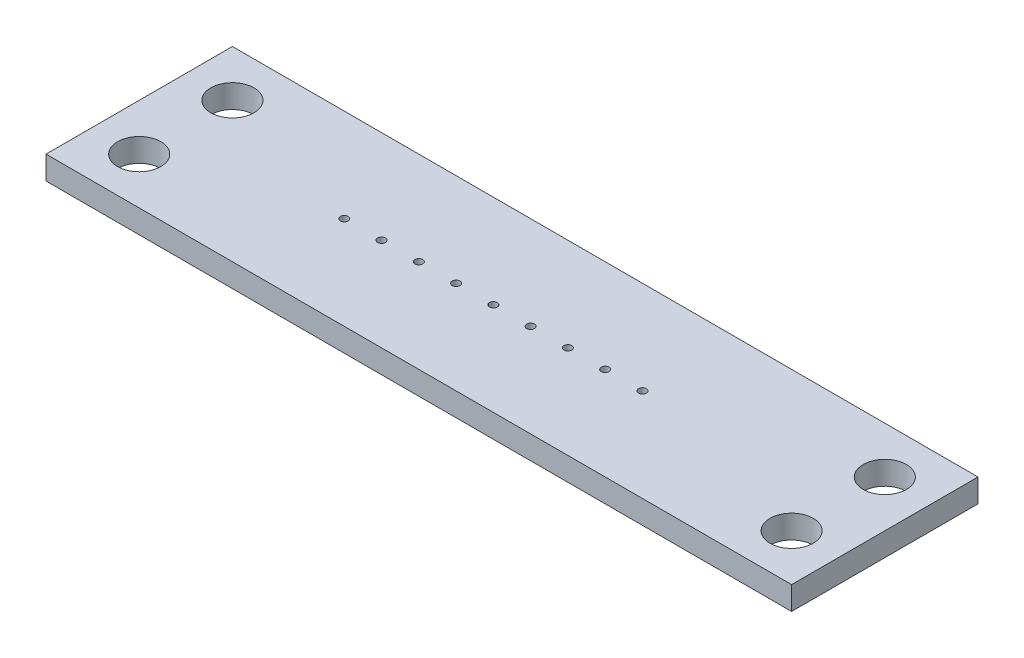
SolidWorks part; units mm, degrees
ref_plane "Front" through (0, 0, 0) normal (0, 0, 1) x (1, 0, 0)
ref_plane "Top" through (0, 0, 0) normal (0, 1, 0) x (1, 0, 0)
ref_plane "Right" through (0, 0, 0) normal (1, 0, 0) x (0, 0, -1)
sketch "Sketch1" plane through (0, 0, 0) normal (0, 1, 0) x (1, 0, 0)
  line L1 (0, 0) -> (50.8, 0)
  line L2 (0, 0) -> (0, 12.7)
  line L3 (0, 12.7) -> (50.8, 12.7)
  line L4 (50.8, 0) -> (50.8, 12.7)
  dimension "D1" = 12.7
  dimension "D2" = 50.8
extrude "Boss-Extrude1" add sketch "Sketch1" along normal blind 1.5875
sketch "Sketch2" plane through (0, 1.5875, 0) normal (0, 1, 0) x (1, 0, 0)
  line L0 (0, 6.35) -> (50.8, 6.35) construction
  line L1 (0, 12.7) -> (0, 0) construction
  line L2 (50.8, 0) -> (50.8, 12.7) construction
  line L3 (50.8, 12.7) -> (0, 12.7) construction
  line L4 (25.4, 12.7) -> (25.4, 0) construction
  line L5 (0, 0) -> (50.8, 0) construction
  circle A0 centre (3.175, 9.525) radius 1.4732
  circle A1 centre (3.175, 3.175) radius 1.4732
  circle A2 centre (47.625, 9.525) radius 1.4732
  circle A3 centre (47.625, 3.175) radius 1.4732
  dimension "D1" = 2.9464
  dimension "D2" = 3.175
  dimension "D3" = 3.175
extrude "Cut-Extrude1" cut sketch "Sketch2" against normal blind 1.5875
sketch "Sketch3" plane through (0, 1.5875, 0) normal (0, 1, 0) x (1, 0, 0)
  line L0 (0, 6.35) -> (50.8, 6.35) construction
  line L1 (0, 12.7) -> (0, 0) construction
  line L2 (50.8, 0) -> (50.8, 12.7) construction
  line L3 (25.4, 0) -> (25.4, 12.7) construction
  line L4 (0, 0) -> (50.8, 0) construction
  line L5 (50.8, 12.7) -> (0, 12.7) construction
  circle A0 centre (24.13, 6.35) radius 0.2667
  circle A1 centre (21.59, 6.35) radius 0.2667
  circle A2 centre (19.05, 6.35) radius 0.2667
  circle A3 centre (16.51, 6.35) radius 0.2667
  circle A4 centre (13.97, 6.35) radius 0.2667
  circle A5 centre (26.67, 6.35) radius 0.2667
  circle A6 centre (29.21, 6.35) radius 0.2667
  circle A7 centre (31.75, 6.35) radius 0.2667
  circle A8 centre (34.29, 6.35) radius 0.2667
  dimension "D1" = 0.5334
  dimension "D2" = 1.27
  dimension "D3" = 5
  dimension "D4" = 5
extrude "Cut-Extrude2" cut sketch "Sketch3" against normal blind 1.5875
